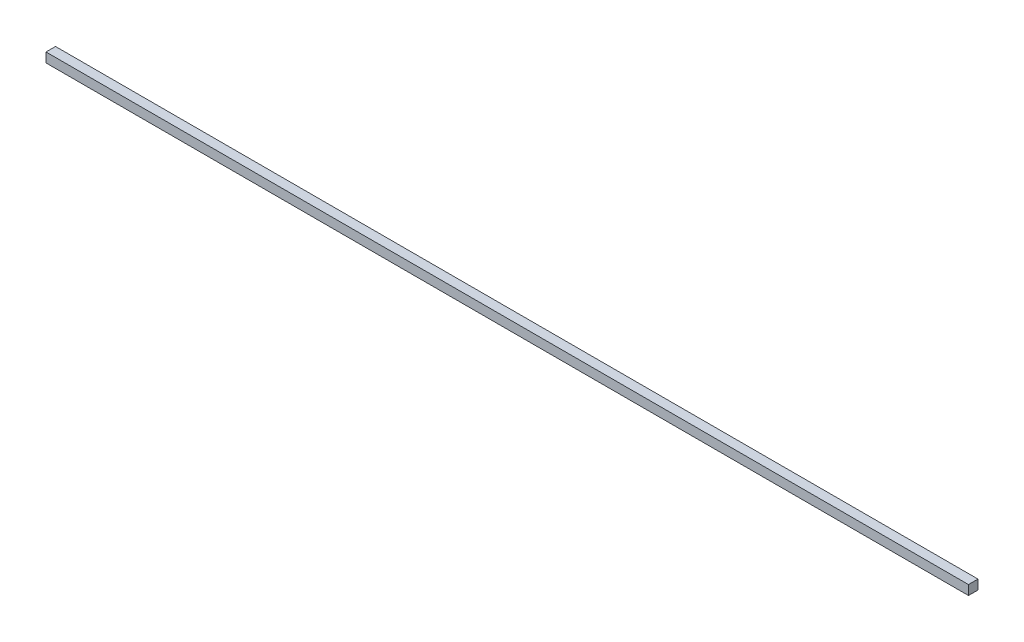
SolidWorks part; units mm, degrees
material "Balsa"
ref_plane "Front Plane" through (0, 0, 0) normal (0, 0, 1) x (1, 0, 0)
ref_plane "Top Plane" through (0, 0, 0) normal (0, 1, 0) x (1, 0, 0)
ref_plane "Right Plane" through (0, 0, 0) normal (1, 0, 0) x (0, 0, -1)
sketch "Sketch1" plane through (0, 0, 0) normal (0, 0, 1) x (1, 0, 0)
  line L1 (0, 0) -> (307.975, 0)
  line L2 (0, 0) -> (0, 3.175)
  line L3 (0, 3.175) -> (307.975, 3.175)
  line L4 (307.975, 0) -> (307.975, 3.175)
  dimension "D1" = 3.175
  dimension "D2" = 307.975
extrude "Boss-Extrude1" add sketch "Sketch1" along normal blind 19.05
sketch "Sketch2" [suppressed] plane through (0, 3.175, 0) normal (0, 1, 0) x (1, 0, 0)
  line L0 (0, -19.05) -> (0, 0) construction
  line L1 (317.5, 0) -> (0, 0)
  line L2 (317.5, 0) -> (317.5, -8.89)
  line L3 (317.5, -8.89) -> (0, -8.89)
  line L4 (0, 0) -> (0, -8.89)
  dimension "D1" = 8.89
extrude "Cut-Extrude1" [suppressed] cut sketch "Sketch2" against normal through all
sketch "Sketch3" [suppressed] plane through (0, 3.175, 0) normal (0, 1, 0) x (1, 0, 0)
  line L0 (0, -19.05) -> (0, 0) construction
  line L1 (307.975, 0) -> (0, 0)
  line L2 (307.975, 0) -> (307.975, -6.35)
  line L3 (307.975, -6.35) -> (0, -6.35)
  line L4 (0, 0) -> (0, -6.35)
  dimension "D1" = 6.35
extrude "Cut-Extrude2" [suppressed] cut sketch "Sketch3" against normal through all
sketch "Sketch4" [suppressed] plane through (0, 3.175, 0) normal (0, 1, 0) x (1, 0, 0)
  line L0 (0, -19.05) -> (0, -6.35) construction
  circle A0 centre (58.7375, -12.7) radius 1.5494
  circle A1 centre (108.7755, -12.7) radius 1.5494
  circle A2 centre (158.8135, -12.7) radius 1.5494
  circle A3 centre (208.8515, -12.7) radius 1.5494
  point P5 (0, -12.7)
  dimension "D1" = 3.0988
  dimension "D3" = 4
extrude "Cut-Extrude3" [suppressed] cut sketch "Sketch4" against normal through all
sketch "Sketch5" [suppressed] plane through (0, 3.175, 0) normal (0, 1, 0) x (1, 0, 0)
  line L2 (0, 0) -> (0, -6.35)
  line L3 (0, -6.35) -> (262.636, -6.35)
  line L5 (0, -19.05) -> (0, 0) construction
  line L6 (317.5, -19.05) -> (262.636, -19.05)
  line L9 (262.636, -19.05) -> (262.636, -6.35)
  line L10 (317.5, -19.05) -> (317.5, 0)
  line L11 (317.5, 0) -> (0, 0)
  dimension "D1" = 6.35
  dimension "D2" = 262.636
extrude "Cut-Extrude4" [suppressed] cut sketch "Sketch5" against normal through all
sketch "Sketch7" [suppressed] plane through (0, 3.175, 0) normal (0, 1, 0) x (1, 0, 0)
  line L2 (0, -19.05) -> (0, -6.35) construction
  circle A0 centre (6.35, -12.7) radius 1.5494
  circle A1 centre (256.35, -12.7) radius 1.5494
  point P5 (0, -12.7)
  dimension "D1" = 3.0988
  dimension "D2" = 6.35
  dimension "D4" = 250
  dimension "D3" = 2
extrude "Cut-Extrude5" [suppressed] cut sketch "Sketch7" against normal through all
sketch "Sketch8" plane through (0, 3.175, 0) normal (0, 1, 0) x (1, 0, 0)
  line L0 (307.975, -19.05) -> (307.975, 0) construction
  line L1 (0, 0) -> (307.975, 0)
  line L2 (0, 0) -> (0, -15.875)
  line L3 (0, -15.875) -> (307.975, -15.875)
  line L4 (307.975, 0) -> (307.975, -15.875)
  dimension "D1" = 15.875
extrude "Cut-Extrude6" cut sketch "Sketch8" against normal up to next
